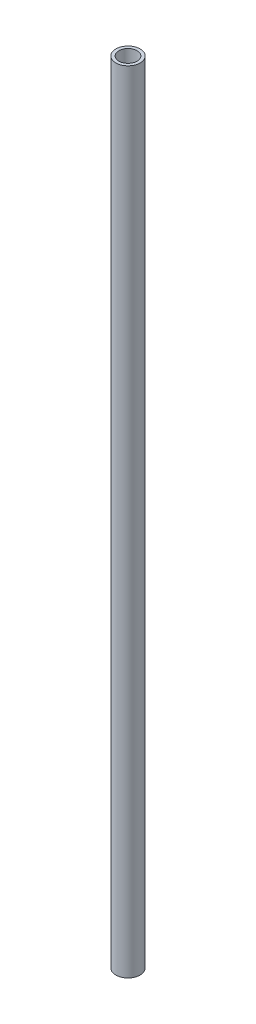
SolidWorks part; units mm, degrees
ref_plane "前视基准面" through (0, 0, 0) normal (0, 0, 1) x (1, 0, 0)
ref_plane "上视基准面" through (0, 0, 0) normal (0, 1, 0) x (1, 0, 0)
ref_plane "右视基准面" through (0, 0, 0) normal (1, 0, 0) x (0, 0, -1)
other "Configuration Table"
sketch "草图1" plane through (0, 0, 0) normal (0, 1, 0) x (1, 0, 0)
  circle A0 centre (0, 0) radius 4
  circle A1 centre (0, 0) radius 3
  dimension "D1" = 8
  dimension "D2" = 6
extrude "凸台-拉伸1" add sketch "草图1" along normal mid plane 260
